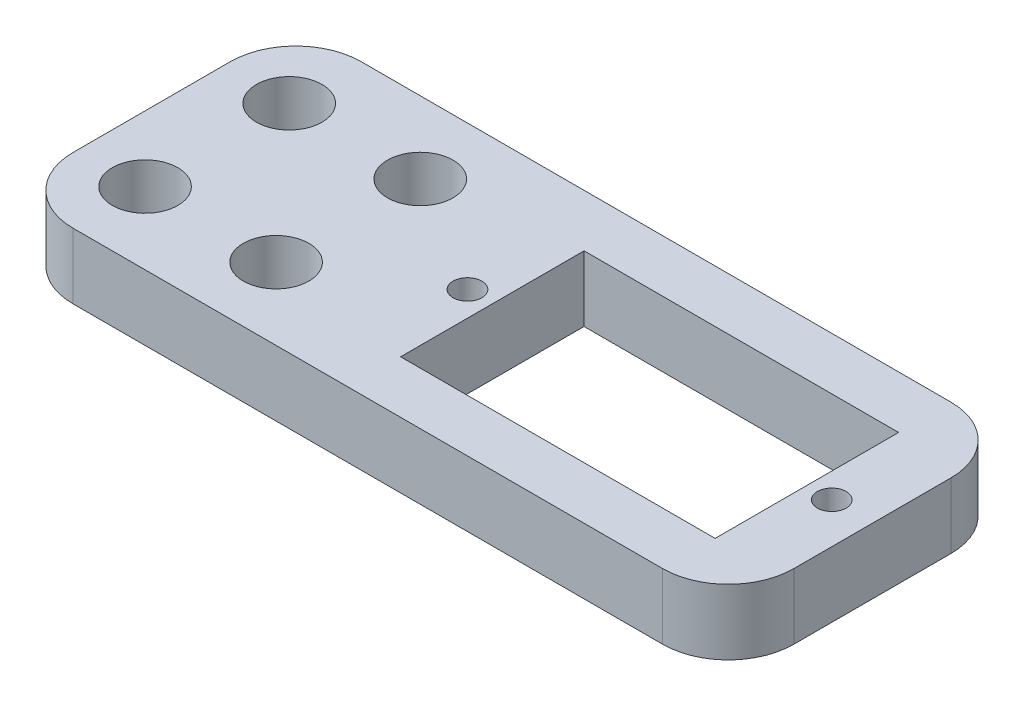
SolidWorks part; units mm, degrees
ref_plane "前视基准面" through (0, 0, 0) normal (0, 0, 1) x (1, 0, 0)
ref_plane "上视基准面" through (0, 0, 0) normal (0, 1, 0) x (1, 0, 0)
ref_plane "右视基准面" through (0, 0, 0) normal (1, 0, 0) x (0, 0, -1)
other "Configuration Table"
sketch "Sketch1" plane through (0, 0, 0) normal (0, 1, 0) x (1, 0, 0)
  line L1 (-30, -11) -> (25, -11)
  line L2 (-30, -11) -> (-30, 11)
  line L3 (-30, 11) -> (25, 11)
  line L5 (-30, -11) -> (25, 9.1667) construction
  line L6 (-30, 11) -> (25, -9.1667) construction
  line L7 (25, 11) -> (25, -11)
  point P0 (0, 0)
  dimension "D1" = 55
  dimension "D2" = 22
extrude "Boss-Extrude1" add sketch "Sketch1" along normal blind 5
sketch "Sketch2" plane through (0, 5, 0) normal (0, 1, 0) x (1, 0, 0)
  line L0 (-30, -11) -> (25, -11) construction
  line L1 (-30, 11) -> (-10, 11) construction
  line L2 (-30, 11) -> (-30, -11) construction
  line L3 (-30, -11) -> (-10, -11)
  line L4 (-10, 11) -> (-10, -11) construction
  line L5 (-30, 0) -> (-10, 0) construction
  line L6 (-20, 11) -> (-20, -11) construction
  line L7 (-20, 0) -> (-20, -11) construction
  line L8 (-20, -11) -> (-20, -5.5) construction
  line L9 (-20, -5.5) -> (-10, -5.5) construction
  line L10 (-10, -5.5) -> (-15, -5.5) construction
  circle A0 centre (-15, -5.5) radius 2.5
  circle A1 centre (-15, 5.5) radius 2.5
  circle A2 centre (-25, -5.5) radius 2.5
  circle A3 centre (-25, 5.5) radius 2.5
  dimension "D2" = 5
  dimension "D1" = 20
extrude "Cut-Extrude1" cut sketch "Sketch2" against normal blind 5 contours A3 | A1 | A2 | A0
fillet "Fillet1" radius 5 4 edges at (-30, 2.5, -11) (-30, 2.5, 11) (25, 2.5, -11) (25, 2.5, 11)
sketch "Sketch4" plane through (0, 5, 0) normal (0, 1, 0) x (1, 0, 0)
  line L0 (0, 0) -> (8, 0) construction
  line L1 (8, 0) -> (21.9, 0) construction
  line L2 (-4, -7) -> (20, -7)
  line L3 (-4, -7) -> (-4, 7)
  line L4 (-4, 7) -> (20, 7)
  line L5 (20, -7) -> (20, 7)
  line L6 (-4, -7) -> (20, 7) construction
  line L7 (-4, 7) -> (20, -7) construction
  line L8 (8, 0) -> (8, 4.7796) construction
  circle A0 centre (21.9, 0) radius 1.1
  circle A1 centre (-5.9, 0) radius 1.1
  dimension "D4" = 2.2
  dimension "D1" = 24
  dimension "D2" = 14
  dimension "D3" = 8
  dimension "D5" = 13.9
extrude "Cut-Extrude2" cut sketch "Sketch4" against normal blind 5 contours L3 L2 L5 L4 | A1 | A0
